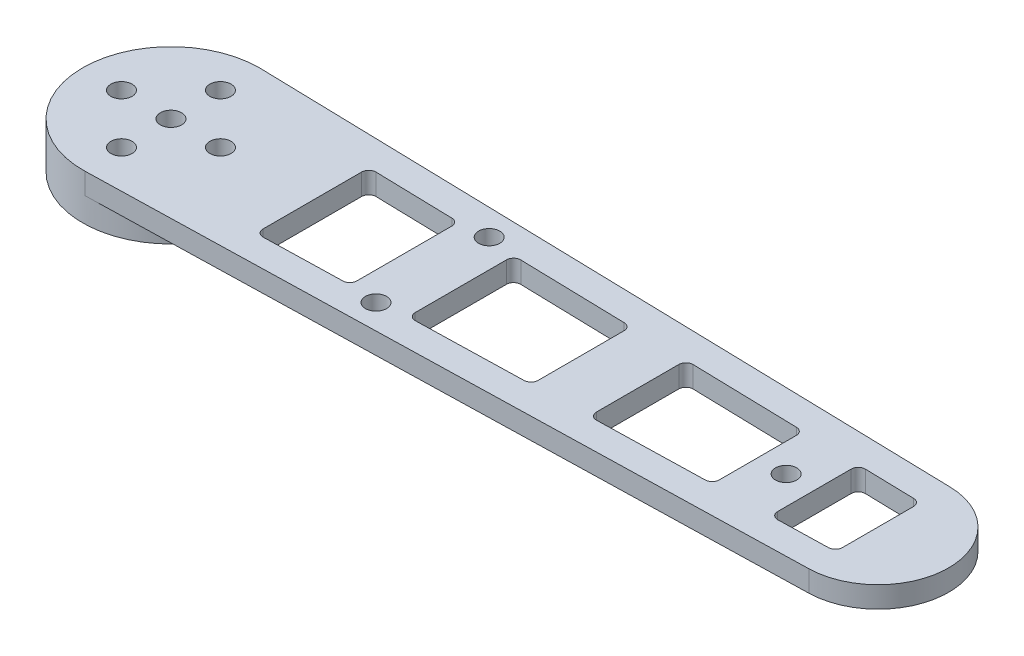
SolidWorks part; units mm, degrees
material "ABS"
ref_plane "前视基准面" through (0, 0, 0) normal (0, 0, 1) x (1, 0, 0)
ref_plane "上视基准面" through (0, 0, 0) normal (0, 1, 0) x (1, 0, 0)
ref_plane "右视基准面" through (0, 0, 0) normal (1, 0, 0) x (0, 0, -1)
sketch "草图1" plane through (0, 0, 0) normal (0, 1, 0) x (1, 0, 0)
  line L0 (-16.855, 0) -> (100, 0) construction
  line L1 (0.3125, 12.4961) -> (100.25, 9.9969)
  line L2 (0.3125, -12.4961) -> (100.25, -9.9969)
  circle A0 centre (0, 0) radius 12.5
  circle A1 centre (100, 0) radius 10
  circle A2 centre (-7, 0) radius 1.5
  circle A3 centre (0, 7) radius 1.5
  circle A4 centre (7, 0) radius 1.5
  circle A5 centre (0, -7) radius 1.5
  circle A6 centre (0, 0) radius 1.5
  dimension "D1" = 25
  dimension "D2" = 100
  dimension "D3" = 20
  dimension "D4" = 7
  dimension "D5" = 3
  dimension "D7" = 3
  dimension "D6" = 4
extrude "凸台-拉伸1" add sketch "草图1" along normal blind 3
sketch "草图2" plane through (0, 0, 0) normal (0, -1, 0) x (1, 0, 0)
  circle A0 centre (0, 0) radius 12.5
  circle A1 centre (0, 0) radius 10
  dimension "D1" = 25
  dimension "D2" = 20
extrude "凸台-拉伸2" add sketch "草图2" along normal blind 3.5 contours A0 | A1
sketch "草图3" plane through (0, 3, 0) normal (0, 1, 0) x (1, 0, 0)
  line L0 (-21.5992, 0) -> (131.7448, 0) construction
  line L1 (20, 8.0025) -> (20, -8.0025)
  line L2 (20, 8.0025) -> (95.3937, 6.1171)
  line L3 (20, -8.0025) -> (100, -6.0019)
  line L4 (0.3125, 12.4961) -> (100.25, 9.9969) construction
  line L5 (0.3125, -12.4961) -> (100.25, -9.9969) construction
  line L6 (33, 7.6774) -> (33, -7.6774)
  line L7 (41, 7.4773) -> (41, -7.4773)
  line L8 (58, 7.0522) -> (58, -7.0522)
  line L9 (66, 6.8521) -> (66, -6.8521)
  line L10 (83, 6.427) -> (83, -6.427)
  line L11 (91, 6.2269) -> (91, -6.2269)
  line L12 (100, -6.0019) -> (100, 6.0019)
  line L13 (95.3937, 6.1171) -> (100, 6.0019)
  circle A1 centre (87, 0) radius 1.5
  circle A2 centre (37, 8) radius 1.5
  circle A3 centre (37, -8) radius 1.5
  point P5 (20, 0)
  dimension "D1" = 20
  dimension "D5" = 8
  dimension "D11" = 100
  dimension "D12" = 3
  dimension "D14" = 3
  dimension "D2" = 4
  dimension "D3" = 33
  dimension "D4" = 8
  dimension "D6" = 37
  dimension "D7" = 58
  dimension "D8" = 8
  dimension "83" = 83
  dimension "D10" = 8
  dimension "D13" = 4
extrude "切除-拉伸1" cut sketch "草图3" against normal blind 10 contours L1 L0 L6 L2 | L0 L1 L3 L6 | L2 A2 | L2 A2 | A3 L3 | A3 L3 | L7 L0 L8 L2 | L0 L7 L3 L8 | L9 L0 L10 L2 | L0 L9 L3 L10 | A1 L0 | L0 A1 | L11 L0 L12 L13 L2 | L0 L11 L3 L12
fillet "圆角1" radius 1 16 edges at (100, 1.5, 6.0019) (91, 1.5, -6.2269) (100, 1.5, -6.0019) (91, 1.5, 6.2269) (66, 1.5, 6.8521) (83, 1.5, 6.427) (83, 1.5, -6.427) (66, 1.5, -6.8521) (41, 1.5, 7.4773) (41, 1.5, -7.4773) (58, 1.5, -7.0522) (58, 1.5, 7.0522) (33, 1.5, 7.6774) (33, 1.5, -7.6774) (20, 1.5, 8.0025) (20, 1.5, -8.0025)
sketch "草图5" plane through (0, 0, 0) normal (0, -1, 0) x (1, 0, 0)
  circle A0 centre (0, 0) radius 10
  circle A1 centre (0, 0) radius 1.5
  circle A2 centre (7, 0) radius 1.5
  circle A4 centre (-7, 0) radius 1.5
  circle A5 centre (0, -7) radius 1.5
  circle A6 centre (0, 7) radius 1.5
extrude "凸台-拉伸3" add sketch "草图5" along normal blind 1
